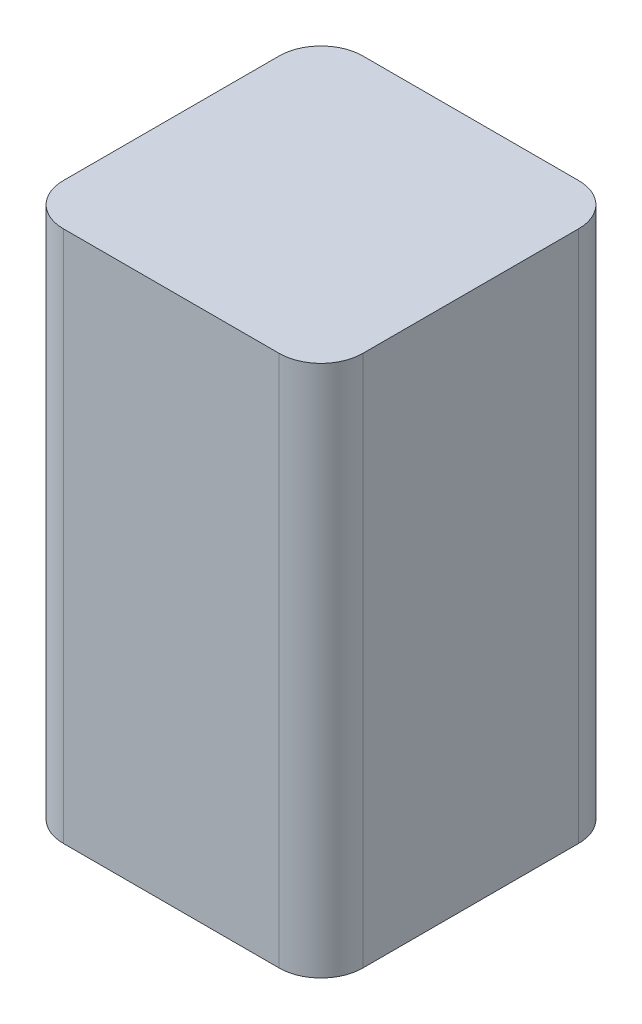
SolidWorks part; units mm, degrees
ref_plane "Front Plane" through (0, 0, 0) normal (0, 0, 1) x (1, 0, 0)
ref_plane "Top Plane" through (0, 0, 0) normal (0, 1, 0) x (1, 0, 0)
ref_plane "Right Plane" through (0, 0, 0) normal (1, 0, 0) x (0, 0, -1)
sketch "Sketch1" plane through (0, 0, 0) normal (0, 1, 0) x (1, 0, 0)
  line L0 (-5, 5) -> (-5, -5)
  line L1 (-5, -5) -> (5, -5)
  line L2 (5, -5) -> (5, 5)
  line L3 (5, 5) -> (-5, 5)
  line L4 (0, -55) -> (0, 55) construction
  line L5 (-55, 0) -> (55, 0) construction
  point P2 (0, 5)
  point P7 (5, 0)
  dimension "D1" = 10
  dimension "D2" = 10
extrude "Boss-Extrude1" add sketch "Sketch1" along normal mid plane 17.78
sketch "Sketch2" plane through (0, -8.89, 0) normal (0, -1, 0) x (1, 0, 0)
  circle A0 centre (0, 0) radius 2.5
extrude "Cut-Extrude1" cut sketch "Sketch2" against normal blind 11.43
fillet "Fillet1" radius 1.397 4 edges at (-5, 0, -5) (5, 0, -5) (5, 0, 5) (-5, 0, 5)
